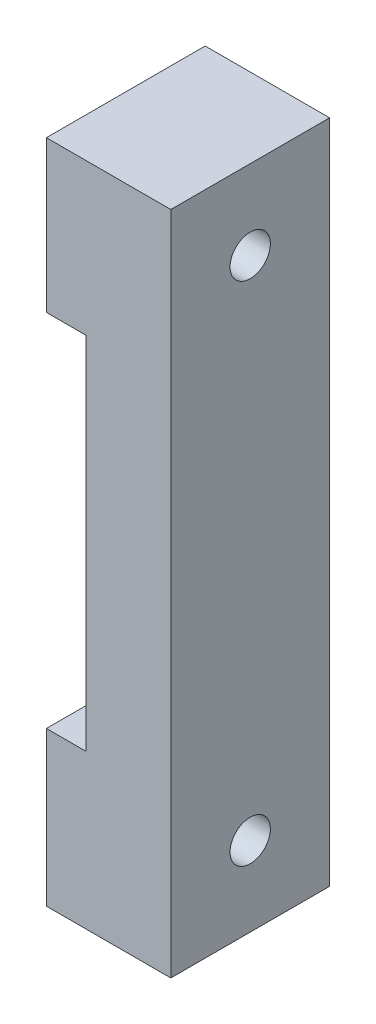
SolidWorks part; units mm, degrees
ref_plane "Front Plane" through (0, 0, 0) normal (0, 0, 1) x (1, 0, 0)
ref_plane "Top Plane" through (0, 0, 0) normal (0, 1, 0) x (1, 0, 0)
ref_plane "Right Plane" through (0, 0, 0) normal (1, 0, 0) x (0, 0, -1)
sketch "Sketch1" plane through (0, 0, 0) normal (0, 0, 1) x (1, 0, 0)
  line L0 (0, 0) -> (19.584, 0)
  line L1 (19.584, 0) -> (19.584, 104.78)
  line L2 (19.584, 104.78) -> (0, 104.78)
  line L3 (0, 104.78) -> (0, 80.95)
  line L4 (0, 80.95) -> (6.27, 80.95)
  line L5 (6.27, 80.95) -> (6.27, 24.23)
  line L6 (6.27, 24.23) -> (0, 24.23)
  line L7 (0, 24.23) -> (0, 0)
  dimension "D1" = 104.78
  dimension "D2" = 19.584
  dimension "D3" = 23.83
  dimension "D4" = 56.72
  dimension "D5" = 6.27
extrude "Boss-Extrude1" add sketch "Sketch1" along normal blind 25
sketch "Sketch2" plane through (0, 0, 0) normal (1, 0, 0) x (0, 0, -1)
  line L0 (-25, 104.78) -> (0, 104.78) construction
  line L1 (-25, 104.78) -> (-25, 80.95) construction
  line L2 (-25, 0) -> (0, 0) construction
  line L3 (0, 52.59) -> (-31.6365, 52.59) construction
  line L4 (0, 80.95) -> (0, 24.23) construction
  line L5 (0, 24.23) -> (0, 0) construction
  circle A0 centre (-12.5, 92.28) radius 3.175
  circle A1 centre (-12.5, 12.5) radius 3.175
  point P0 (-12.5, 92.28)
  point P9 (-12.25, 52.39)
  point P12 (-12.5, 12.5)
  dimension "D3" = 52.39
  dimension "D6" = 6.35
  dimension "D7" = 6.35
  dimension "D1" = 12.5
  dimension "D2" = 12.5
  dimension "D4" = 12.5
  dimension "D5" = 12.5
extrude "Cut-Extrude1" cut sketch "Sketch2" along normal blind 40
